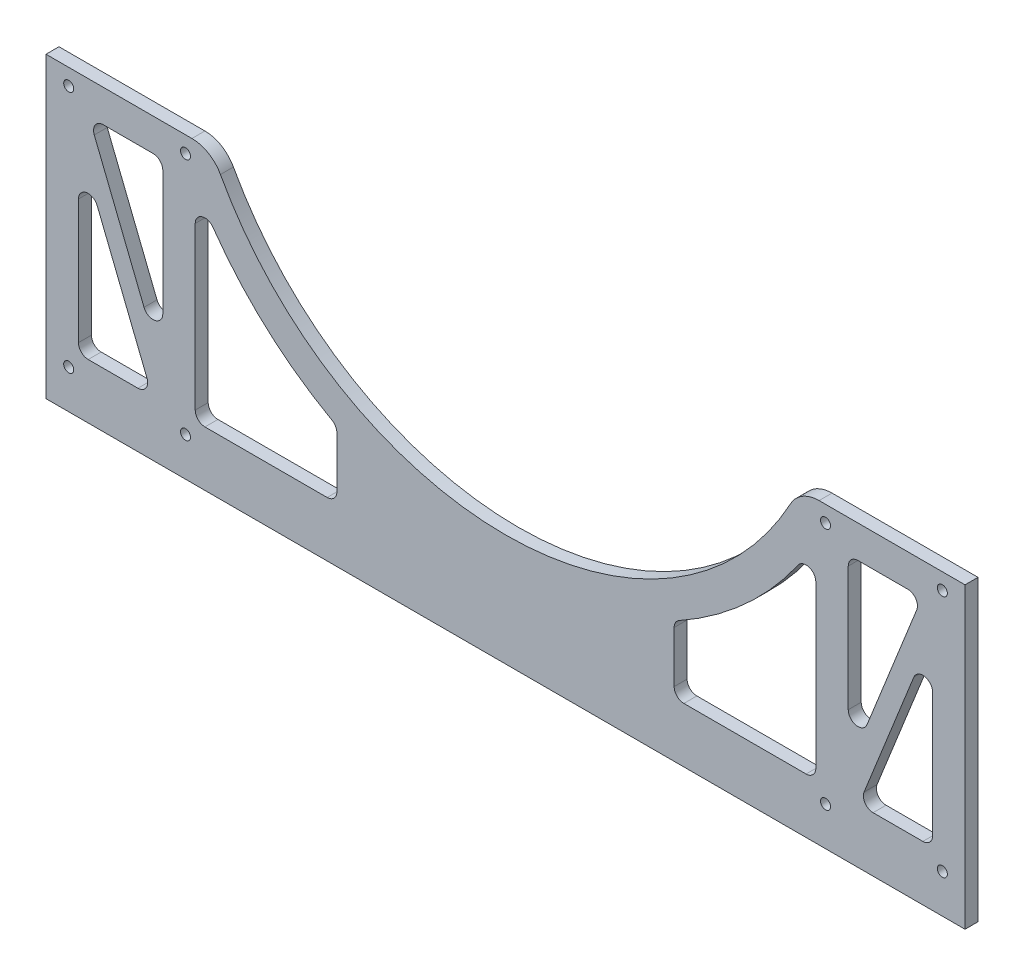
SolidWorks part; units mm, degrees
ref_plane "Front" through (0, 0, 0) normal (0, 0, 1) x (1, 0, 0)
ref_plane "Top" through (0, 0, 0) normal (0, 1, 0) x (1, 0, 0)
ref_plane "Right" through (0, 0, 0) normal (1, 0, 0) x (0, 0, -1)
sketch "Sketch1" plane through (0, 0, 0) normal (0, 0, 1) x (1, 0, 0)
  line L0 (0, 85) -> (0, 0) construction
  line L1 (-141.65, -42.5) -> (141.65, -42.5)
  line L2 (-141.65, -42.5) -> (-141.65, 42.5)
  line L3 (-141.65, 42.5) -> (141.65, 42.5)
  line L4 (141.65, -42.5) -> (141.65, 42.5)
  line L5 (-141.65, -42.5) -> (141.65, 42.5) construction
  line L6 (-141.65, 42.5) -> (141.65, -42.5) construction
  circle A0 centre (0, 85) radius 100
  point P0 (0, 0)
  dimension "D3" = 200
  dimension "D1" = 283.3
  dimension "D2" = 85
  dimension "D4" = 85
extrude "Boss-Extrude1" add sketch "Sketch1" along normal blind 4 contours A0 L3 L2 L1 L4
sketch "Sketch2" plane through (0, 0, 4) normal (0, 0, 1) x (1, 0, 0)
  line L5 (-131.65, 8.8445) -> (-131.65, -29.5)
  line L6 (-128.65, -32.5) -> (-113.3122, -32.5)
  line L9 (-108.65, 32.5) -> (-123.9878, 32.5)
  line L10 (-90.5193, 42.5) -> (-141.65, 42.5)
  line L11 (-141.65, 42.5) -> (-141.65, -42.5)
  line L12 (-141.65, -42.5) -> (141.65, -42.5)
  line L13 (141.65, -42.5) -> (141.65, 42.5)
  line L14 (141.65, 42.5) -> (90.5193, 42.5)
  line L15 (-90.5193, 42.5) -> (-141.65, 42.5)
  line L16 (-141.65, 42.5) -> (-141.65, -42.5)
  line L17 (-141.65, -42.5) -> (141.65, -42.5)
  line L18 (141.65, -42.5) -> (141.65, 42.5)
  line L19 (141.65, 42.5) -> (90.5193, 42.5)
  line L20 (-105.65, 29.5) -> (-105.65, -8.8445)
  line L21 (-131.65, 32.5) -> (-105.65, -32.5)
  line L22 (-125.8646, 9.9587) -> (-110.5268, -28.3858)
  line L23 (-126.7732, 28.3858) -> (-111.4354, -9.9587)
  line L24 (-128.8646, 33.6142) -> (-102.8646, -31.3858) construction
  line L25 (-96.6631, 32.5) -> (-131.65, 32.5) construction
  line L26 (-134.4354, 31.3858) -> (-108.4354, -33.6142) construction
  line L27 (-131.65, 32.5) -> (-131.65, -32.5) construction
  line L28 (-92.65, -32.5) -> (-54.9846, -32.5)
  line L29 (-131.65, -32.5) -> (131.65, -32.5) construction
  line L30 (0, 0) -> (0, -66.6903) construction
  line L31 (-95.65, 20.3086) -> (-95.65, -29.5)
  line L32 (-51.9846, -29.5) -> (-51.9846, -13.7203)
  line L33 (51.9846, -29.5) -> (51.9846, -13.7203)
  line L34 (131.65, 32.5) -> (96.6631, 32.5) construction
  line L35 (131.65, -32.5) -> (131.65, 32.5) construction
  line L36 (95.65, 20.3086) -> (95.65, -29.5)
  line L37 (92.65, -32.5) -> (54.9846, -32.5)
  line L38 (126.7732, 28.3858) -> (111.4354, -9.9587)
  line L39 (125.8646, 9.9587) -> (110.5268, -28.3858)
  line L40 (131.65, 32.5) -> (105.65, -32.5)
  line L41 (105.65, 29.5) -> (105.65, -8.8445)
  line L42 (141.65, 42.5) -> (141.65, -42.5)
  line L43 (90.5193, 42.5) -> (141.65, 42.5)
  line L44 (108.65, 32.5) -> (123.9878, 32.5)
  line L45 (128.65, -32.5) -> (113.3122, -32.5)
  line L46 (131.65, 8.8445) -> (131.65, -29.5)
  circle A0 centre (134.65, -37.5) radius 1.55
  arc A1 (-90.1903, 22.0261) -> (-53.5248, -11.0994) centre (0, 85) ccw
  arc A2 (-90.5193, 42.5) -> (90.5193, 42.5) centre (0, 85) ccw
  arc A3 (-90.5193, 42.5) -> (90.5193, 42.5) centre (0, 85) ccw
  arc A4 (-128.65, -32.5) -> (-131.65, -29.5) centre (-128.65, -29.5) cw
  arc A5 (-110.5268, -28.3858) -> (-113.3122, -32.5) centre (-113.3122, -29.5) cw
  arc A6 (-111.4354, -9.9587) -> (-105.65, -8.8445) centre (-108.65, -8.8445) ccw
  arc A7 (-105.65, 29.5) -> (-108.65, 32.5) centre (-108.65, 29.5) ccw
  arc A8 (-126.7732, 28.3858) -> (-123.9878, 32.5) centre (-123.9878, 29.5) cw
  arc A9 (-125.8646, 9.9587) -> (-131.65, 8.8445) centre (-128.65, 8.8445) ccw
  arc A10 (-96.6631, 32.5) -> (96.6631, 32.5) centre (0, 85) ccw construction
  arc A11 (-95.65, -29.5) -> (-92.65, -32.5) centre (-92.65, -29.5) ccw
  arc A12 (-51.9846, -29.5) -> (-54.9846, -32.5) centre (-54.9846, -29.5) cw
  arc A13 (-51.9846, -13.7203) -> (-53.5248, -11.0994) centre (-54.9846, -13.7203) ccw
  arc A14 (-95.65, 20.3086) -> (-90.1903, 22.0261) centre (-92.65, 20.3086) cw
  arc A15 (95.65, 20.3086) -> (90.1903, 22.0261) centre (92.65, 20.3086) ccw
  arc A16 (51.9846, -13.7203) -> (53.5248, -11.0994) centre (54.9846, -13.7203) cw
  arc A17 (51.9846, -29.5) -> (54.9846, -32.5) centre (54.9846, -29.5) ccw
  arc A18 (95.65, -29.5) -> (92.65, -32.5) centre (92.65, -29.5) cw
  arc A19 (125.8646, 9.9587) -> (131.65, 8.8445) centre (128.65, 8.8445) cw
  arc A20 (126.7732, 28.3858) -> (123.9878, 32.5) centre (123.9878, 29.5) ccw
  arc A21 (105.65, 29.5) -> (108.65, 32.5) centre (108.65, 29.5) cw
  arc A22 (111.4354, -9.9587) -> (105.65, -8.8445) centre (108.65, -8.8445) cw
  arc A23 (110.5268, -28.3858) -> (113.3122, -32.5) centre (113.3122, -29.5) ccw
  arc A24 (128.65, -32.5) -> (131.65, -29.5) centre (128.65, -29.5) ccw
  arc A25 (90.1903, 22.0261) -> (53.5248, -11.0994) centre (0, 85) cw
  circle A26 centre (-134.65, 37.5) radius 1.55
  circle A27 centre (-98.65, 37.5) radius 1.55
  circle A28 centre (-98.65, -37.5) radius 1.55
  circle A29 centre (-134.65, -37.5) radius 1.55
  circle A30 centre (98.65, -37.5) radius 1.55
  circle A31 centre (98.65, 37.5) radius 1.55
  circle A32 centre (134.65, 37.5) radius 1.55
  point P2 (-105.65, 10.3277)
  dimension "D6" = 3
  dimension "D7" = 3
  dimension "D9" = 3.1
  dimension "D10" = 7
  dimension "D11" = 5
  dimension "D12" = 7
  dimension "D13" = 75
  dimension "D3" = 36
  dimension "D8" = 10
  dimension "D1" = 0
  dimension "D2" = 10
  dimension "D4" = 3
  dimension "D5" = 3
extrude "Cut-Extrude1" cut sketch "Sketch2" against normal blind 10 contours L22 A9 L5 A4 L6 A5 | A8 L23 A6 L20 A7 L9 | A14 L31 A11 L28 A12 L32 A13 A1 | A15 A25 A16 L33 A17 L37 A18 L36 | A22 L38 A20 L44 A21 L41 | L45 A24 L46 A19 L39 A23 | A26 | A27 | A28 | A29 | A30 | A0 | A31 | A32
fillet "Fillet1" radius 10 2 edges at (-90.5193, 42.5, 2) (90.5193, 42.5, 2)
sketch "Sketch3" plane through (0, -42.5, 0) normal (0, -1, 0) x (1, 0, 0)
  line L4 (-141.65, 0) -> (141.65, 0)
  line L5 (141.65, 0) -> (141.65, 4)
  line L6 (141.65, 4) -> (-141.65, 4)
  line L7 (-141.65, 4) -> (-141.65, 0)
  line L8 (-141.65, 0) -> (141.65, 0)
  line L9 (141.65, 0) -> (141.65, 4)
  line L10 (141.65, 4) -> (-141.65, 4)
  line L11 (-141.65, 4) -> (-141.65, 0)
  dimension "D1" = 0
extrude "Boss-Extrude2" add sketch "Sketch3" along normal up to surface (6.9588 mm away)
